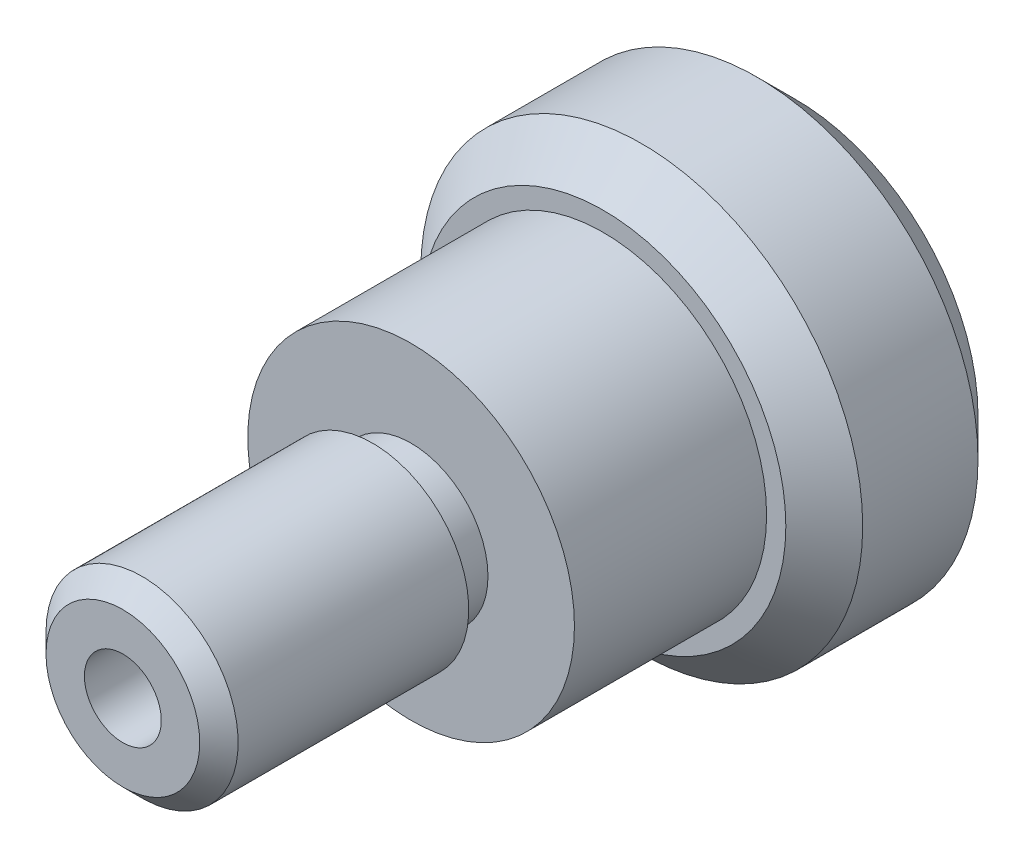
SolidWorks part; units mm, degrees
ref_plane "前视基准面" through (0, 0, 0) normal (0, 0, 1) x (1, 0, 0)
ref_plane "上视基准面" through (0, 0, 0) normal (0, 1, 0) x (1, 0, 0)
ref_plane "右视基准面" through (0, 0, 0) normal (1, 0, 0) x (0, 0, -1)
sketch "草图1" plane through (0, 0, 0) normal (0, 0, 1) x (1, 0, 0)
  circle A0 centre (0, 0) radius 11.5
  dimension "D1" = 23
extrude "拉伸1" add sketch "草图1" along normal blind 10
sketch "草图2" plane through (0, 0, 10) normal (0, 0, 1) x (1, 0, 0)
  circle A0 centre (0, 0) radius 8.5
  dimension "D1" = 17
extrude "拉伸2" add sketch "草图2" along normal blind 10
sketch "草图3" plane through (0, 0, 20) normal (0, 0, 1) x (1, 0, 0)
  circle A0 centre (0, 0) radius 4
  dimension "D1" = 8
extrude "拉伸3" add sketch "草图3" along normal blind 2
sketch "草图4" plane through (0, 0, 22) normal (0, 0, 1) x (1, 0, 0)
  circle A0 centre (0, 0) radius 5
  dimension "D1" = 10
extrude "拉伸4" add sketch "草图4" along normal blind 13
cosmetic thread "装饰螺纹线1" parameters "D2"=8
sketch "草图6" plane through (0, 0, 0) normal (0, 1, 0) x (1, 0, 0)
  line L0 (0, -2.1701) -> (0, -35.965) construction
  line L1 (0, -35) -> (2, -35)
  line L2 (-5, -35) -> (5, -35) construction
  line L3 (2, -35) -> (2, -15)
  line L4 (2, -15) -> (0, -13.8453)
  line L5 (0, -35) -> (0, -13.8453)
  dimension "D1" = 60
  dimension "D2" = 20
  dimension "D3" = 4
revolve "切除-旋转1" cut sketch "草图6" angle 360 about L0
sketch "草图7" plane through (0, 0, 0) normal (0, 1, 0) x (1, 0, 0)
  line L0 (-16.3409, -15) -> (6.1891, -15) construction
  line L1 (-8.5, -15) -> (-8.5, -17)
  line L2 (-8.5, -17) -> (3.5, -17)
  line L3 (3.5, -17) -> (4.6547, -15)
  line L4 (-8.5, -20) -> (8.5, -20) construction
  line L5 (-8.5, -15) -> (4.6547, -15)
  line L6 (-8.5, -10) -> (-8.5, -20) construction
  dimension "D1" = 60
  dimension "D2" = 4
  dimension "D3" = 5
  dimension "D4" = 12
revolve "切除-旋转2" cut sketch "草图7" angle 360 about L0
chamfer "倒角1" distance 2 angle 45 2 edges at (11.5, 0, 10) (11.5, 0, 0)
chamfer "倒角2" distance 1 angle 45 1 edges at (5, 0, 35)
